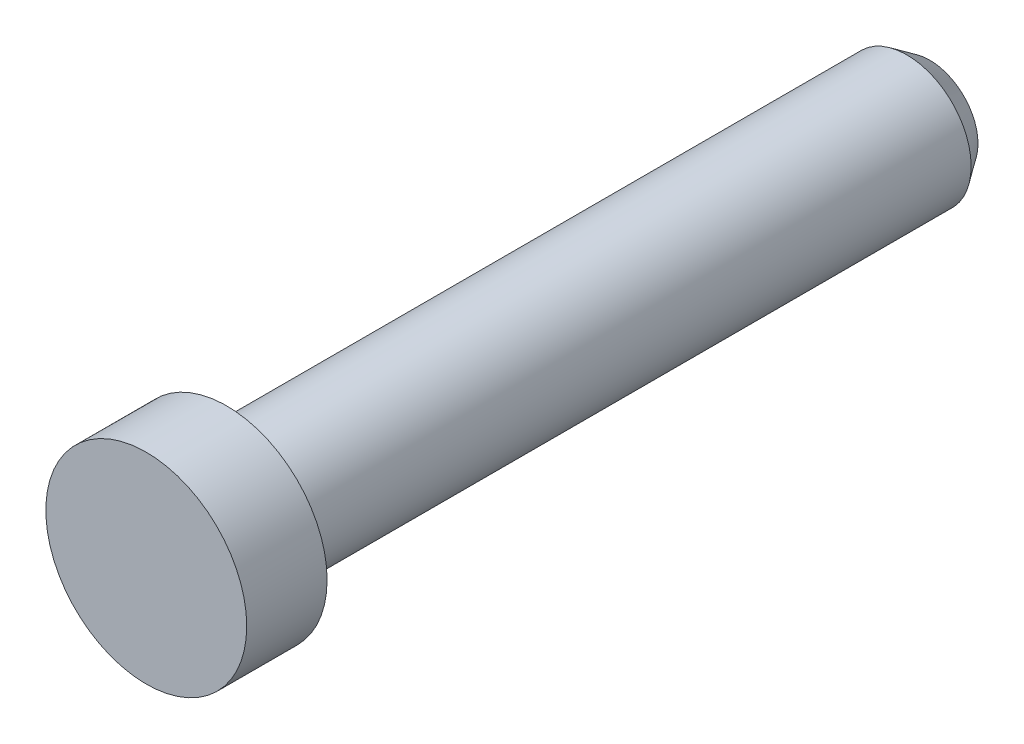
SolidWorks part; units mm, degrees
ref_plane "Front Plane" through (0, 0, 0) normal (0, 0, 1) x (1, 0, 0)
ref_plane "Top Plane" through (0, 0, 0) normal (0, 1, 0) x (1, 0, 0)
ref_plane "Right Plane" through (0, 0, 0) normal (1, 0, 0) x (0, 0, -1)
sketch "Sketch1" plane through (0, 0, 0) normal (0, 0, 1) x (1, 0, 0)
  circle A0 centre (0, 0) radius 1.6
  dimension "D1" = 3.2
extrude "Boss-Extrude1" add sketch "Sketch1" along normal mid plane 17.5 contours A0
chamfer "Chamfer1" distance 0.4 angle 55 1 edges at (1.6, 0, -8.75)
sketch "Sketch2" plane through (0, 0, 8.75) normal (0, 0, 1) x (1, 0, 0)
  circle A0 centre (0, 0) radius 2.5
  dimension "D1" = 5
extrude "Boss-Extrude2" add sketch "Sketch2" along normal blind 2
equation "\"JansenLegThickness\"= 5mm"
equation "\"PegLength@Boss-Extrude1\" = \"JansenLegThickness\" * 3 + 2.5mm"
